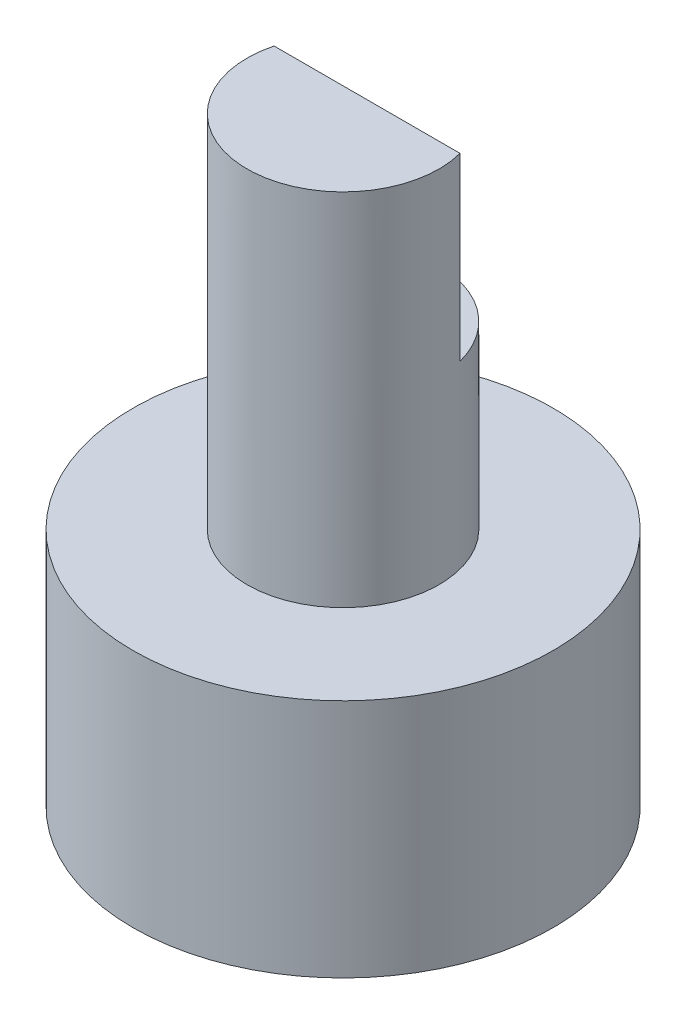
SolidWorks part; units mm, degrees
ref_plane "Front Plane" through (0, 0, 0) normal (0, 0, 1) x (1, 0, 0)
ref_plane "Top Plane" through (0, 0, 0) normal (0, 1, 0) x (1, 0, 0)
ref_plane "Right Plane" through (0, 0, 0) normal (1, 0, 0) x (0, 0, -1)
sketch "Sketch1" plane through (0, 0, 0) normal (0, 1, 0) x (1, 0, 0)
  circle A0 centre (0, 0) radius 7
  dimension "D1" = 14
extrude "Boss-Extrude1" add sketch "Sketch1" along normal blind 8
sketch "Sketch2" plane through (0, 8, 0) normal (0, 1, 0) x (1, 0, 0)
  circle A0 centre (0, 0) radius 3.2
  dimension "D1" = 6.4
extrude "Boss-Extrude2" add sketch "Sketch2" along normal blind 12
sketch "Sketch3" plane through (0, 20, 0) normal (0, 1, 0) x (1, 0, 0)
  line L0 (-3.0984, 0.8) -> (3.0984, 0.8)
  line L1 (-3.0984, 0.8) -> (-3.0984, 4.0051)
  line L2 (0, -3.2) -> (3.5756, -3.2) construction
  line L3 (-3.0984, 4.0051) -> (3.0984, 4.0051)
  line L4 (3.0984, 4.0051) -> (3.0984, 0.8)
  circle A0 centre (0, 0) radius 3.2 construction
  circle A1 centre (0, 0) radius 3.2 construction
  dimension "D1" = 4
extrude "Cut-Extrude1" cut sketch "Sketch3" against normal blind 6
sketch "Sketch4" plane through (0, 0, 0) normal (0, -1, 0) x (1, 0, 0)
  circle A0 centre (0, 0) radius 1.25
  dimension "D1" = 2.5
extrude "Cut-Extrude2" cut sketch "Sketch4" against normal blind 10
